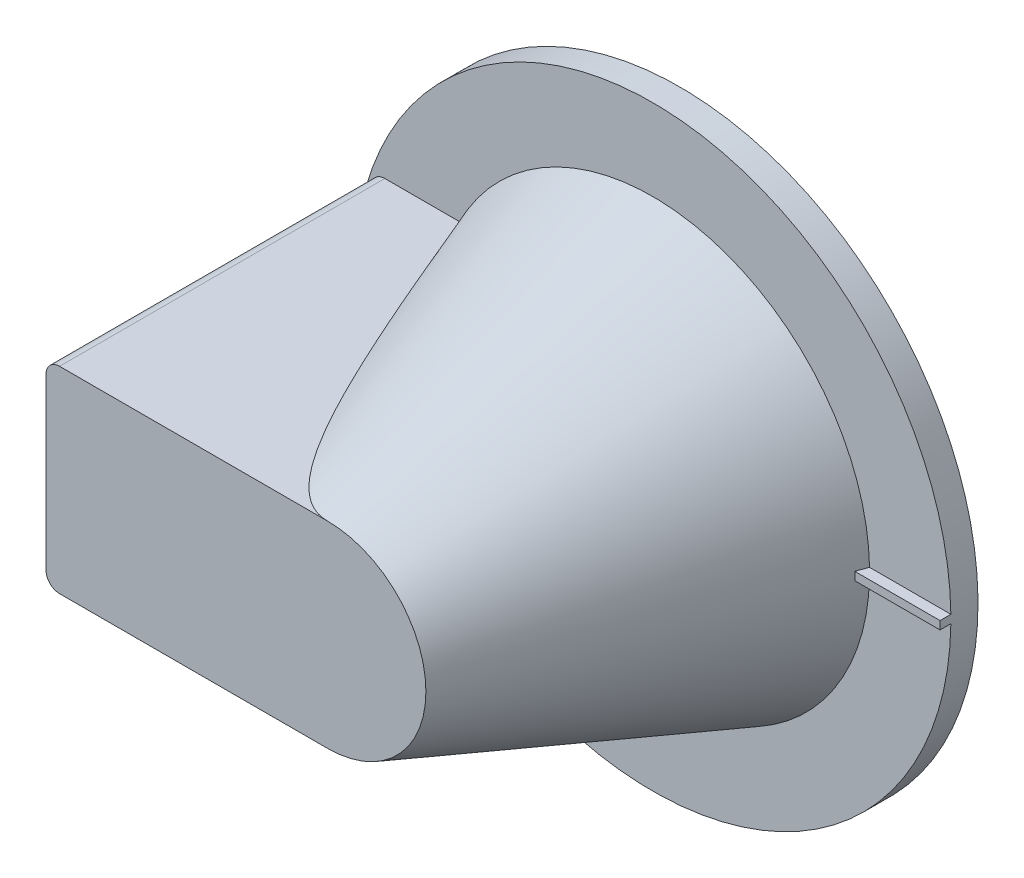
SolidWorks part; units mm, degrees
ref_plane "Front Plane" through (0, 0, 0) normal (0, 0, 1) x (1, 0, 0)
ref_plane "Top Plane" through (0, 0, 0) normal (0, 1, 0) x (1, 0, 0)
ref_plane "Right Plane" through (0, 0, 0) normal (1, 0, 0) x (0, 0, -1)
sketch "Sketch1" plane through (0, 0, 0) normal (0, 0, 1) x (1, 0, 0)
  circle A0 centre (0, 0) radius 11
  dimension "D1" = 22
extrude "Boss-Extrude1" add sketch "Sketch1" along normal blind 1
sketch "Sketch2" plane through (0, 0, 1) normal (0, 0, 1) x (1, 0, 0)
  circle A0 centre (0, 0) radius 8
  dimension "D1" = 16
extrude "Boss-Extrude2" add sketch "Sketch2" along normal blind 12 draft 20
sketch "Sketch3" plane through (0, 0, 13) normal (0, 0, 1) x (1, 0, 0)
  line L0 (0, 3.6324) -> (-9.883, 3.6324)
  line L1 (0, -3.6324) -> (-9.883, -3.6324)
  line L2 (-10.383, 3.1324) -> (-10.383, -3.1324)
  circle A0 centre (0, 0) radius 3.6324 construction
  arc A1 (0, -3.6324) -> (0, 3.6324) centre (0, 0) ccw
  circle A2 centre (0, 0) radius 11 construction
  arc A3 (-9.883, -3.6324) -> (-10.383, -3.1324) centre (-9.883, -3.1324) cw
  arc A4 (-9.883, 3.6324) -> (-10.383, 3.1324) centre (-9.883, 3.1324) ccw
  point P10 (-10.383, -3.6324)
  point P13 (-10.383, 3.6324)
  dimension "D1" = 0.5
extrude "Boss-Extrude3" add sketch "Sketch3" against normal up to next
sketch "Sketch4" plane through (0, 0, 1) normal (0, 0, 1) x (1, 0, 0)
  line L0 (8, 0) -> (11, 0) construction
  line L3 (10.999, 0.15) -> (7.4985, 0.15)
  line L4 (10.999, -0.15) -> (7.4985, -0.15)
  arc A0 (-7.1278, -3.6324) -> (-7.1278, 3.6324) centre (0, 0) ccw construction
  circle A1 centre (0, 0) radius 11 construction
  arc A3 (10.999, -0.15) -> (10.999, 0.15) centre (0, 0) ccw
  arc A4 (-7.1278, -3.6324) -> (-7.1278, 3.6324) centre (0, 0) ccw construction
  arc A5 (7.4985, -0.15) -> (7.4985, 0.15) centre (0, 0) ccw
  arc A6 (-7.1278, -3.6324) -> (-6.6823, -3.4053) centre (-6.9051, -3.5188) cw
  arc A7 (-7.1278, 3.6324) -> (-6.6823, 3.4053) centre (-6.9051, 3.5188) ccw
  arc A8 (-6.6823, -3.4053) -> (-6.6823, 3.4053) centre (0, 0) ccw construction
  circle M9 centre (0, 0) radius 11
  arc M10 (-7.1278, 3.6324) -> (-7.1278, -3.6324) centre (0, 0) cw
  dimension "D2" = 0.15
  dimension "D3" = 0.15
  dimension "D1" = 0.5
extrude "Indicador Seleccion" add sketch "Sketch4" along normal blind 0.4 contours A5 L4 L3 M10 | L4 L3 M9 M10
sketch "Sketch5" plane through (0, 0, 0) normal (0, 0, -1) x (-1, 0, 0)
  line L0 (0, 0) -> (0, 6.2989) construction
  line L1 (0, 0) -> (0, 2.75) construction
  arc A0 (-1.9413, 1.9478) -> (-2.2553, 1.5736) centre (0, 0) ccw
  arc A1 (0.2351, 2.7399) -> (-0.2351, 2.7399) centre (0, 2.825) ccw
  arc A2 (1.158, 2.4943) -> (0.7162, 2.6551) centre (0.9662, 2.6546) ccw
  arc A3 (1.9413, 1.9478) -> (1.5811, 2.25) centre (1.8159, 2.1641) ccw
  arc A4 (2.4904, 1.1664) -> (2.2553, 1.5736) centre (2.4465, 1.4125) ccw
  arc A5 (2.7391, 0.2443) -> (2.6575, 0.7073) centre (2.7821, 0.4906) ccw
  arc A6 (2.6575, -0.7073) -> (2.7391, -0.2443) centre (2.7821, -0.4906) ccw
  arc A7 (2.2553, -1.5736) -> (2.4904, -1.1664) centre (2.4465, -1.4125) ccw
  arc A8 (1.5811, -2.25) -> (1.9413, -1.9478) centre (1.8159, -2.1641) ccw
  arc A9 (0.7162, -2.6551) -> (1.158, -2.4943) centre (0.9662, -2.6546) ccw
  arc A10 (-0.2351, -2.7399) -> (0.2351, -2.7399) centre (0, -2.825) ccw
  arc A11 (-1.158, -2.4943) -> (-0.7162, -2.6551) centre (-0.9662, -2.6546) ccw
  arc A12 (-1.9413, -1.9478) -> (-1.5811, -2.25) centre (-1.8159, -2.1641) ccw
  arc A13 (-2.4904, -1.1664) -> (-2.2553, -1.5736) centre (-2.4465, -1.4125) ccw
  arc A14 (-2.7391, -0.2443) -> (-2.6575, -0.7073) centre (-2.7821, -0.4906) ccw
  arc A15 (-2.6575, 0.7073) -> (-2.7391, 0.2443) centre (-2.7821, 0.4906) ccw
  arc A16 (-2.2553, 1.5736) -> (-2.4904, 1.1664) centre (-2.4465, 1.4125) ccw
  arc A17 (-1.5811, 2.25) -> (-1.9413, 1.9478) centre (-1.8159, 2.1641) ccw
  arc A18 (-0.7162, 2.6551) -> (-1.158, 2.4943) centre (-0.9662, 2.6546) ccw
  arc A19 (-1.158, 2.4943) -> (-1.5811, 2.25) centre (0, 0) ccw
  arc A20 (-0.2351, 2.7399) -> (-0.7162, 2.6551) centre (0, 0) ccw
  arc A21 (0.7162, 2.6551) -> (0.2351, 2.7399) centre (0, 0) ccw
  arc A22 (1.5811, 2.25) -> (1.158, 2.4943) centre (0, 0) ccw
  arc A23 (2.2553, 1.5736) -> (1.9413, 1.9478) centre (0, 0) ccw
  arc A24 (2.6575, 0.7073) -> (2.4904, 1.1664) centre (0, 0) ccw
  arc A25 (2.7391, -0.2443) -> (2.7391, 0.2443) centre (0, 0) ccw
  arc A26 (2.4904, -1.1664) -> (2.6575, -0.7073) centre (0, 0) ccw
  arc A27 (1.9413, -1.9478) -> (2.2553, -1.5736) centre (0, 0) ccw
  arc A28 (1.158, -2.4943) -> (1.5811, -2.25) centre (0, 0) ccw
  arc A29 (0.2351, -2.7399) -> (0.7162, -2.6551) centre (0, 0) ccw
  arc A30 (-0.7162, -2.6551) -> (-0.2351, -2.7399) centre (0, 0) ccw
  arc A31 (-1.5811, -2.25) -> (-1.158, -2.4943) centre (0, 0) ccw
  arc A32 (-2.2553, -1.5736) -> (-1.9413, -1.9478) centre (0, 0) ccw
  arc A33 (-2.6575, -0.7073) -> (-2.4904, -1.1664) centre (0, 0) ccw
  arc A34 (-2.7391, 0.2443) -> (-2.7391, -0.2443) centre (0, 0) ccw
  arc A35 (-2.4904, 1.1664) -> (-2.6575, 0.7073) centre (0, 0) ccw
extrude "Cut-Extrude1" cut sketch "Sketch5" against normal blind 8
sketch "Sketch6" plane through (0, 0, 0) normal (0, 0, -1) x (-1, 0, 0)
  circle A0 centre (0, 0) radius 3.5
  dimension "D1" = 7
extrude "Cut-Extrude2" cut sketch "Sketch6" against normal blind 0.6
chamfer "Chamfer1" distance 0.5 angle 30 18 edges at (-2.5842, 0.9406, 0.6) (-2.1066, -1.7677, 0.6) (-2.5842, -0.9406, 0.6) (-2.75, 0, 0.6) (-2.1066, 1.7677, 0.6) (-1.375, 2.3816, 0.6) (-0.4775, 2.7082, 0.6) (0.4775, 2.7082, 0.6) (1.375, 2.3816, 0.6) (2.1066, 1.7677, 0.6) (2.5842, 0.9406, 0.6) (2.75, 0, 0.6) (2.5842, -0.9406, 0.6) (2.1066, -1.7677, 0.6) (1.375, -2.3816, 0.6) (0.4775, -2.7082, 0.6) (-0.4775, -2.7082, 0.6) (-1.375, -2.3816, 0.6)
equation "\"D3@Sketch4\"=\"D2@Sketch4\""
